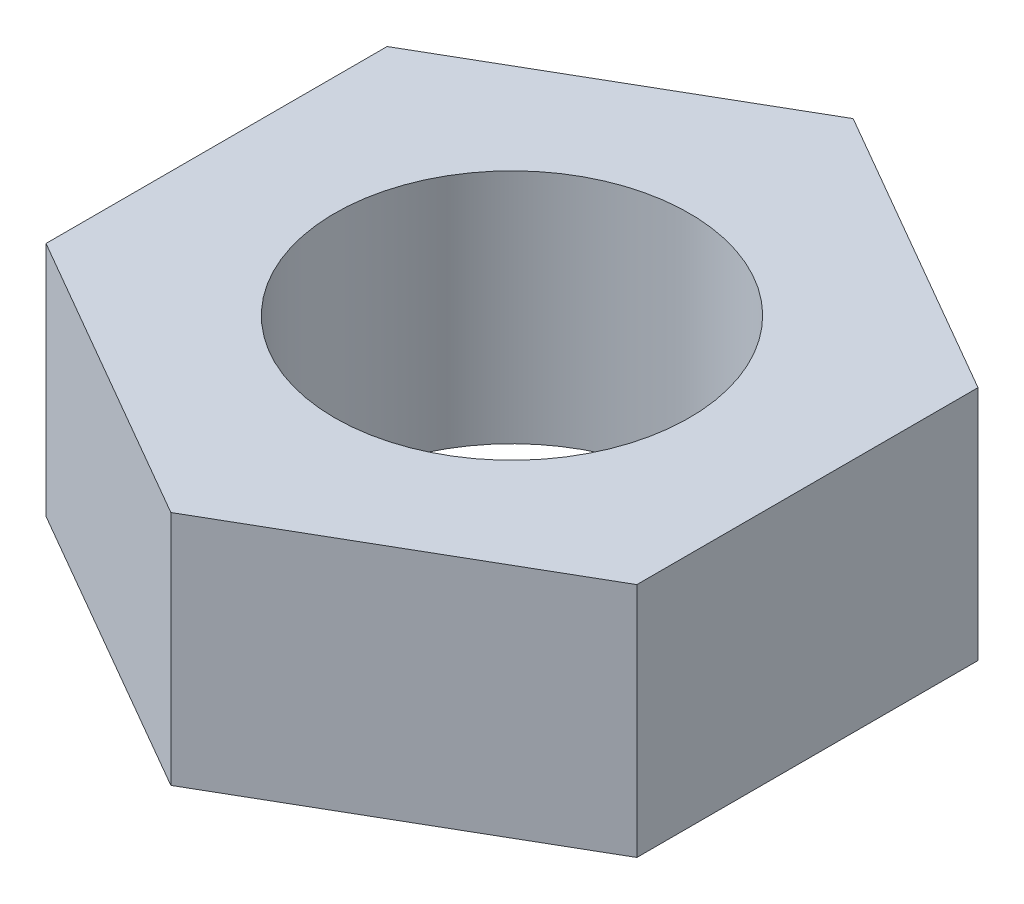
SolidWorks part; units mm, degrees
ref_plane "Front Plane" through (0, 0, 0) normal (0, 0, 1) x (1, 0, 0)
ref_plane "Top Plane" through (0, 0, 0) normal (0, 1, 0) x (1, 0, 0)
ref_plane "Right Plane" through (0, 0, 0) normal (1, 0, 0) x (0, 0, -1)
sketch "Sketch1" plane through (0, 0, 0) normal (0, 1, 0) x (1, 0, 0)
  line L1 (0, 2.8868) -> (-2.5, 1.4434)
  line L2 (-2.5, 1.4434) -> (-2.5, -1.4434)
  line L3 (-2.5, -1.4434) -> (0, -2.8868)
  line L4 (0, -2.8868) -> (2.5, -1.4434)
  line L5 (2.5, -1.4434) -> (2.5, 1.4434)
  line L6 (2.5, 1.4434) -> (0, 2.8868)
  circle A0 centre (0, 0) radius 1.5
  circle A1 centre (0, 0) radius 2.5 construction
  dimension "D1" = 3
  dimension "D2" = 5
extrude "Boss-Extrude1" add sketch "Sketch1" along normal blind 2
